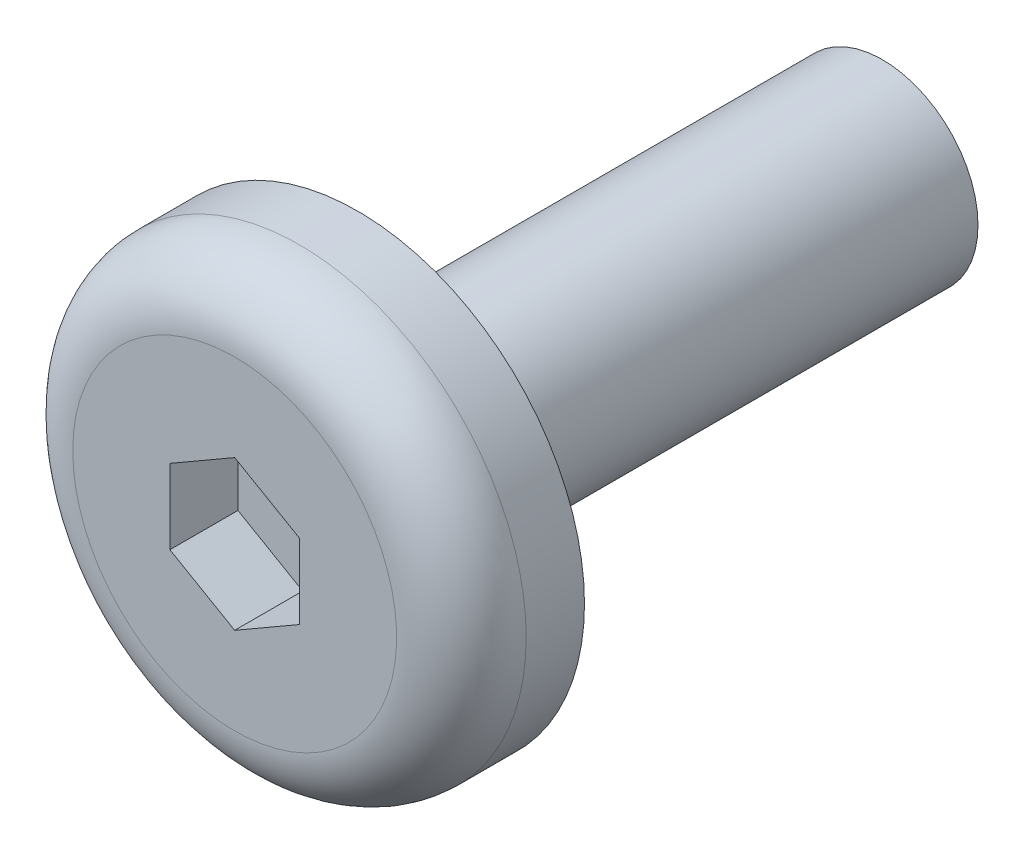
SolidWorks part; units mm, degrees
material "Chrome Stainless Steel"
ref_plane "Front Plane" through (0, 0, 0) normal (0, 0, 1) x (1, 0, 0)
ref_plane "Top Plane" through (0, 0, 0) normal (0, 1, 0) x (1, 0, 0)
ref_plane "Right Plane" through (0, 0, 0) normal (1, 0, 0) x (0, 0, -1)
sketch "Sketch1" plane through (0, 0, 0) normal (1, 0, 0) x (0, 0, -1)
  line L0 (1.9, 1.475) -> (1.9, 3.5)
  line L1 (0, 0) -> (10, 0)
  line L3 (1.9, 1.475) -> (10, 1.475)
  line L4 (10, 0) -> (10, 1.475)
  line L5 (1.9, 3.5) -> (0, 3.5)
  line L6 (0, 3.5) -> (0, 0)
  dimension "D1" = 10
  dimension "D2" = 1.475
  dimension "D3" = 3.5
  dimension "D4" = 1.9
revolve "Revolve1" add sketch "Sketch1" angle 360 about L1
fillet "Fillet1" radius 1 1 edges at (3.5, 0, 0)
sketch "Sketch2" plane through (0, 0, 0) normal (0, 0, 1) x (1, 0, 0)
  line L1 (0, 1.1547) -> (-1, 0.5774)
  line L2 (-1, 0.5774) -> (-1, -0.5774)
  line L3 (-1, -0.5774) -> (0, -1.1547)
  line L4 (0, -1.1547) -> (1, -0.5774)
  line L5 (1, -0.5774) -> (1, 0.5774)
  line L6 (1, 0.5774) -> (0, 1.1547)
  circle A0 centre (0, 0) radius 1 construction
  dimension "D1" = 2
extrude "Cut-Extrude1" cut sketch "Sketch2" against normal blind 1.05
